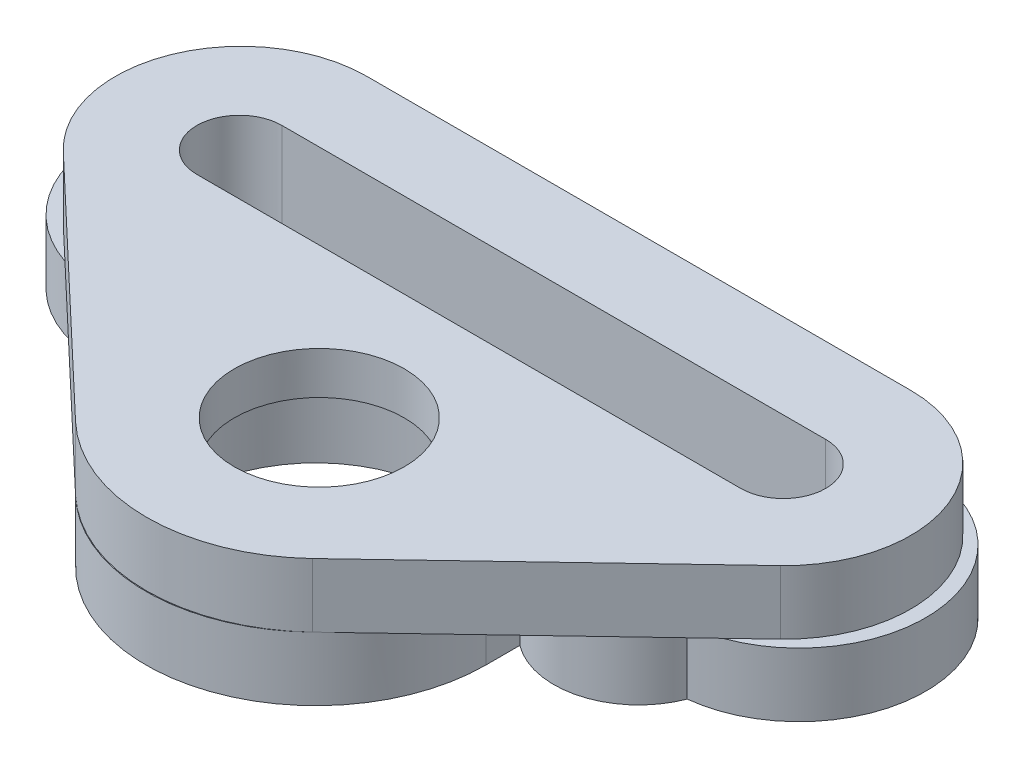
SolidWorks part; units mm, degrees
ref_plane "Płaszczyzna przednia" through (0, 0, 0) normal (0, 0, 1) x (1, 0, 0)
ref_plane "Płaszczyzna górna" through (0, 0, 0) normal (0, 1, 0) x (1, 0, 0)
ref_plane "Płaszczyzna prawa" through (0, 0, 0) normal (1, 0, 0) x (0, 0, -1)
sketch "Szkic2" plane through (0, 0, 0) normal (0, 1, 0) x (1, 0, 0)
  line L0 (-16, 0) -> (16, 0)
  line L1 (0, 0) -> (0, -5) construction
  line L2 (-16, -5) -> (16, -5)
  line L3 (16, 0) -> (16, 5) construction
  line L4 (16, -5) -> (16, -10) construction
  line L5 (-16, 0) -> (-16, 5) construction
  line L6 (-16, -5) -> (-16, -10) construction
  line L7 (-16, 5) -> (16, 5)
  line L9 (-18.5, -2.5) -> (18.5, -2.5) construction
  line L10 (0, -2.5) -> (0, -14) construction
  line L11 (-16, -5) -> (-13, -5) construction
  line L12 (-13, -5) -> (-13, -8) construction
  line L13 (16, -5) -> (13, -5) construction
  line L14 (13, -5) -> (13, -8) construction
  line L15 (-13, -8) -> (-18, -8) construction
  line L16 (-13, -8) -> (-8, -8) construction
  line L17 (13, -8) -> (8, -8) construction
  line L18 (13, -8) -> (18, -8) construction
  line L19 (0, -14) -> (-10, -14) construction
  line L20 (0, -14) -> (10, -14) construction
  line L21 (-10, -14) -> (-10, -12.0576)
  line L22 (10, -14) -> (10, -12)
  arc A0 (-16, 0) -> (-16, -5) centre (-16, -2.5) ccw
  arc A1 (16, 0) -> (16, -5) centre (16, -2.5) cw
  arc A2 (16, 5) -> (17.6604, -9.8113) centre (16.8302, -2.4057) cw
  arc A3 (-16, 5) -> (-17.6779, -9.8924) centre (-16.839, -2.4462) ccw
  circle A4 centre (0, -14) radius 7.5
  circle A5 centre (-13, -8) radius 2.4
  circle A6 centre (13, -8) radius 2.4
  arc A7 (-17.6779, -9.8924) -> (-10, -12.0576) centre (-13, -8) ccw
  arc A9 (-10, -14) -> (10, -14) centre (0, -14) ccw
  arc A10 (10, -12) -> (17.6604, -9.8113) centre (13, -8) ccw
  point P4 (0, 0)
  point P10 (0, -5)
  dimension "D9" = 15
  dimension "D12" = 4.8
  dimension "D14" = 4.8
  dimension "D1" = 32
  dimension "D2" = 5
  dimension "D3" = 32
  dimension "D4" = 5
  dimension "D5" = 5
  dimension "D6" = 5
  dimension "D7" = 5
  dimension "D8" = 11.5
  dimension "D10" = 3
  dimension "D11" = 3
  dimension "D13" = 3
  dimension "D15" = 3
  dimension "D16" = 5
  dimension "D17" = 5
  dimension "D18" = 5
  dimension "D19" = 5
  dimension "D20" = 10
  dimension "D21" = 10
extrude "Dodanie-wyciągnięcie1" add sketch "Szkic2" along normal blind 3.75
sketch "Szkic3" plane through (0, 3.75, 0) normal (0, 1, 0) x (1, 0, 0)
  line L0 (0, 0) -> (0, -13.8) construction
  line L1 (16, 0) -> (-16, 0) construction
  line L2 (-16, 0) -> (16, 0)
  line L3 (-16, -5) -> (16, -5)
  line L4 (-16, 5) -> (16, 5)
  line L5 (16, -5) -> (16, -10) construction
  line L6 (-16, -5) -> (-16, -10) construction
  line L7 (-21.0938, -7.7678) -> (-6.9685, -21.1721)
  line L8 (-6.9685, -21.1721) -> (6.9685, -21.1721) construction
  line L9 (-21.0539, -2.5) -> (21.0539, -2.5) construction
  line L10 (-21.0938, -7.7678) -> (21.0938, -7.7678) construction
  line L11 (21.0938, -7.7678) -> (6.9685, -21.1721)
  arc A0 (-16, 5) -> (-21.0938, -7.7678) centre (-16, -2.4) ccw
  circle A1 centre (0, -13.8) radius 5
  arc A2 (-16, 0) -> (-16, -5) centre (-16, -2.5) ccw
  arc A3 (16, 0) -> (16, -5) centre (16, -2.5) cw
  arc A4 (16, 5) -> (21.0938, -7.7678) centre (16, -2.4) cw
  arc A5 (-10, -14) -> (10, -14) centre (0, -14) ccw construction
  arc A6 (-6.9685, -21.1721) -> (6.9685, -21.1721) centre (0, -13.8288) ccw
  point P9 (0, 0)
  dimension "D2" = 10
  dimension "D1" = 13.8
  dimension "D3" = 5
  dimension "D4" = 5
  dimension "D5" = 5.0539
  dimension "D6" = 5.0539
  dimension "D7" = 19.4731
extrude "Dodanie-wyciągnięcie2" add sketch "Szkic3" along normal blind 3.75
sketch "Szkic9" plane through (0, 0, 0) normal (0, -1, 0) x (1, 0, 0)
  line L0 (0, 21.5) -> (0, 6.5) construction
  circle A0 centre (0, 14) radius 7.5 construction
  circle A1 centre (0, 14) radius 7.5
extrude "Wytnij-wyciągnięcie3" cut sketch "Szkic9" against normal blind 5
sketch "Szkic10" plane through (0, 0, 0) normal (0, -1, 0) x (1, 0, 0)
  line L0 (-15.4, 8) -> (-10.6, 8) construction
  line L1 (-10.6, 8) -> (15.4, 8) construction
  circle A0 centre (-13, 8) radius 2.4 construction
  circle A1 centre (-13, 8) radius 2.4 construction
  circle A2 centre (13, 8) radius 2.4 construction
  circle A3 centre (-13, 8) radius 2.5
  circle A4 centre (13, 8) radius 2.5
  dimension "D1" = 5
  dimension "D2" = 5
extrude "Wytnij-wyciągnięcie4" cut sketch "Szkic10" against normal blind 6.5
